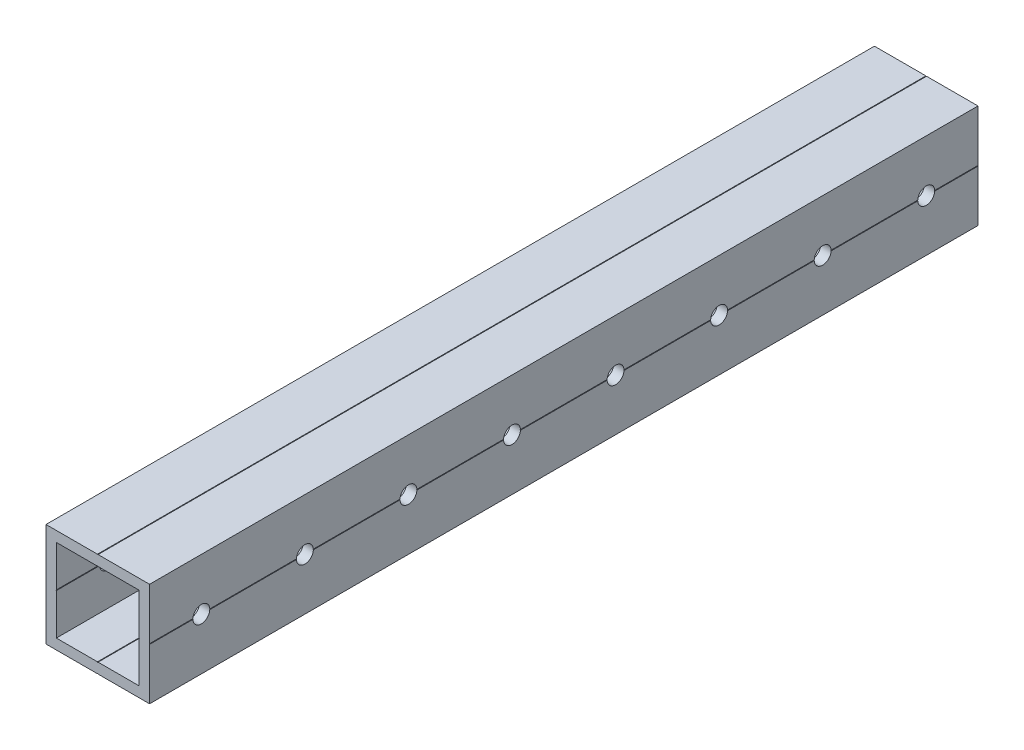
SolidWorks part; units mm, degrees
ref_plane "Front Plane" through (0, 0, 0) normal (0, 0, 1) x (1, 0, 0)
ref_plane "Top Plane" through (0, 0, 0) normal (0, 1, 0) x (1, 0, 0)
ref_plane "Right Plane" through (0, 0, 0) normal (1, 0, 0) x (0, 0, -1)
ref_plane "Plane1" through (0, -12.7, 0) normal (0, -1, 0) x (1, 0, 0)
sketch "Sketch1" plane through (0, -12.7, 0) normal (0, -1, 0) x (1, 0, 0)
  line L0 (12.7, 749.3) -> (-12.7, 749.3)
  line L1 (-12.7, 749.3) -> (-12.7, -749.3)
  line L2 (-12.7, -749.3) -> (12.7, -749.3)
  line L3 (12.7, -749.3) -> (12.7, 749.3)
extrude "Boss-Extrude1" add sketch "Sketch1" against normal blind 25.4
sketch "Sketch2" plane through (0, 0, 749.3) normal (0, 0, 1) x (1, 0, 0)
  line L0 (0.0762, 12.7) -> (-0.0762, 12.7)
  line L1 (-0.0762, 12.7) -> (0.0762, 12.5476)
  line L2 (0.0762, 12.5476) -> (0.0762, 12.7)
extrude "Cut-Extrude1" cut sketch "Sketch2" against normal through all
sketch "Sketch3" plane through (0, 0, 749.3) normal (0, 0, 1) x (1, 0, 0)
  line L0 (12.7, 0.0762) -> (12.5476, -0.0762)
  line L1 (12.5476, -0.0762) -> (12.7, -0.0762)
  line L2 (12.7, -0.0762) -> (12.7, 0.0762)
extrude "Cut-Extrude2" cut sketch "Sketch3" against normal blind 1498.6
sketch "Sketch4" plane through (0, 0, 749.3) normal (0, 0, 1) x (1, 0, 0)
  line L0 (-0.0762, -12.7) -> (0.0762, -12.7)
  line L1 (0.0762, -12.7) -> (-0.0762, -12.5476)
  line L2 (-0.0762, -12.5476) -> (-0.0762, -12.7)
extrude "Cut-Extrude3" cut sketch "Sketch4" against normal through all
sketch "Sketch5" plane through (0, 0, 749.3) normal (0, 0, 1) x (1, 0, 0)
  line L0 (-12.7, -0.0762) -> (-12.5476, -0.0762)
  line L1 (-12.5476, -0.0762) -> (-12.7, 0.0762)
  line L2 (-12.7, 0.0762) -> (-12.7, -0.0762)
extrude "Cut-Extrude4" cut sketch "Sketch5" against normal through all
sketch "Sketch6" plane through (0, 0, 749.3) normal (0, 0, 1) x (1, 0, 0)
  line L0 (-10.16, -10.16) -> (-0.0762, -10.16)
  line L1 (-0.0762, -10.16) -> (0.0762, -10.3124)
  line L2 (0.0762, -10.3124) -> (0.0762, -10.16)
  line L3 (0.0762, -10.16) -> (10.16, -10.16)
  line L4 (10.16, -10.16) -> (10.16, -0.0762)
  line L5 (10.16, -0.0762) -> (10.3124, 0.0762)
  line L6 (10.3124, 0.0762) -> (10.16, 0.0762)
  line L7 (10.16, 0.0762) -> (10.16, 10.16)
  line L8 (10.16, 10.16) -> (0.0762, 10.16)
  line L9 (0.0762, 10.16) -> (-0.0762, 10.3124)
  line L10 (-0.0762, 10.3124) -> (-0.0762, 10.16)
  line L11 (-0.0762, 10.16) -> (-10.16, 10.16)
  line L12 (-10.16, 10.16) -> (-10.16, 0.0762)
  line L13 (-10.16, 0.0762) -> (-10.3124, 0.0762)
  line L14 (-10.3124, 0.0762) -> (-10.16, -0.0762)
  line L15 (-10.16, -0.0762) -> (-10.16, -10.16)
extrude "Cut-Extrude5" cut sketch "Sketch6" against normal through all
draft "Draft1" type of draft neutral plane draft angle 45 faces to draft 1 face at (0.0762, 12.6238, 0) neutral plane through (0, 12.7, 0) neutral plane normal (0, 1, 0) parameters "D1"=45
draft "Draft2" type of draft neutral plane draft angle 45 faces to draft 1 face at (12.6238, -0.0762, 0) neutral plane through (12.7, 12.7, -749.3) neutral plane normal (1, 0, 0) parameters "D1"=45
draft "Draft3" type of draft neutral plane draft angle 45 faces to draft 1 face at (-0.0762, -12.6238, 0) neutral plane through (0, -12.7, 0) neutral plane normal (0, -1, 0) parameters "D1"=45
draft "Draft4" type of draft neutral plane draft angle 45 faces to draft 1 face at (-12.6238, -0.0762, 0) neutral plane through (-12.7, 12.7, 749.3) neutral plane normal (-1, 0, 0) parameters "D1"=45
draft "Draft5" type of draft neutral plane draft angle 45 faces to draft 1 face at (0.0762, -10.2362, 0) neutral plane through (0.0762, -10.16, -749.3) neutral plane normal (0, 1, 0) parameters "D1"=45
draft "Draft6" type of draft neutral plane draft angle 45 faces to draft 1 face at (10.2362, 0.0762, 0) neutral plane through (10.16, 0.0762, -749.3) neutral plane normal (-1, 0, 0) parameters "D1"=45
draft "Draft7" type of draft neutral plane draft angle 45 faces to draft 1 face at (-0.0762, 10.2362, 0) neutral plane through (-0.0762, 10.16, -749.3) neutral plane normal (0, -1, 0) parameters "D1"=45
draft "Draft8" type of draft neutral plane draft angle 45 faces to draft 1 face at (-10.2362, 0.0762, 0) neutral plane through (-10.16, 10.16, -749.3) neutral plane normal (1, 0, 0) parameters "D1"=45
hole_wizard "#6 Clearance Hole1" positions "Sketch8" profile "Sketch7" hole size "#6" standard "ANSI Inch"
sketch "Sketch8" plane through (12.7, 0, 0) normal (1, 0, 0) x (0, 0, -1)
  point P0 (736.3704, 0.6595)
  point P1 (711.2, 0)
  point P2 (685.8, 0)
  point P3 (660.4, 0)
  point P4 (635, 0)
  point P5 (609.6, 0)
  point P6 (584.2, 0)
  point P7 (558.8, 0)
  point P8 (533.4, 0)
  point P9 (508, 0)
  point P10 (482.6, 0)
  point P11 (457.2, 0)
  point P12 (431.8, 0)
  point P13 (406.4, 0)
  point P14 (381, 0)
  point P15 (355.6, 0)
  point P16 (330.2, 0)
  point P17 (304.8, 0)
  point P18 (279.4, 0)
  point P19 (254, 0)
  point P20 (228.6, 0)
  point P21 (203.2, 0)
  point P22 (177.8, 0)
  point P23 (152.4, 0)
  point P24 (127, 0)
  point P25 (101.6, 0)
  point P26 (76.2, 0)
  point P27 (50.8, 0)
  point P28 (25.4, 0)
  point P29 (0, 0)
  point P30 (-25.4, 0)
  point P31 (-50.8, 0)
  point P32 (-76.2, 0)
  point P33 (-101.6, 0)
  point P34 (-127, 0)
  point P35 (-152.4, 0)
  point P36 (-177.8, 0)
  point P37 (-203.2, 0)
  point P38 (-228.6, 0)
  point P39 (-254, 0)
  point P40 (-279.4, 0)
  point P41 (-304.8, 0)
  point P42 (-330.2, 0)
  point P43 (-355.6, 0)
  point P44 (-381, 0)
  point P45 (-406.4, 0)
  point P46 (-431.8, 0)
  point P47 (-457.2, 0)
  point P48 (-482.6, 0)
  point P49 (-508, 0)
  point P50 (-533.4, 0)
  point P51 (-558.8, 0)
  point P52 (-584.2, 0)
  point P53 (-609.6, 0)
  point P54 (-635, 0)
  point P55 (-660.4, 0)
  point P56 (-685.8, 0)
  point P57 (-711.2, 0)
  point P58 (-736.6, 0)
sketch "Sketch7" plane through (12.7, 0.6595, -736.3704) normal (0, 1, 0) x (0, 0, -1)
  line L0 (0, 0) -> (0, 25.4)
  line L1 (0, 25.4) -> (2.0701, 25.4)
  line L2 (2.0701, 25.4) -> (2.0701, 0)
  line L5 (2.0701, 0) -> (0, 0)
  line L10 (0, 25.4) -> (-2.0701, 25.4) construction
  line L11 (0, -6.35) -> (0, 107.95) construction
  dimension "Hole Dia." = 4.1402
  dimension "Hole Depth" = 25.4
  dimension "Drill Angle" = 180
sketch "Sketch9" plane through (0, 0, 0) normal (1, 0, 0) x (0, 0, -1)
  line L0 (-749.3, -0.0762) -> (-749.3, -12.7) construction
  line L1 (-520.7, 180.4075) -> (828.8057, 180.4075)
  line L2 (-520.7, 180.4075) -> (-520.7, -148.1313)
  line L3 (-520.7, -148.1313) -> (828.8057, -148.1313)
  line L4 (828.8057, 180.4075) -> (828.8057, -148.1313)
  point P6 (828.8057, -148.1313)
  dimension "D1" = 228.6
extrude "Cut-Extrude6" cut sketch "Sketch9" against normal blind 27.94 and the other way blind 27.94
sketch "Sketch10" plane through (0, 0, 0) normal (1, 0, 0) x (0, 0, -1)
  line L0 (-749.3, -0.0762) -> (-749.3, -12.7) construction
  line L1 (-546.1, 60.0847) -> (-326.607, 60.0847)
  line L2 (-546.1, 60.0847) -> (-546.1, -123.2349)
  line L3 (-546.1, -123.2349) -> (-326.607, -123.2349)
  line L4 (-326.607, 60.0847) -> (-326.607, -123.2349)
  dimension "D1" = 203.2
extrude "Cut-Extrude7" cut sketch "Sketch10" against normal blind 27.94 and the other way blind 27.94
